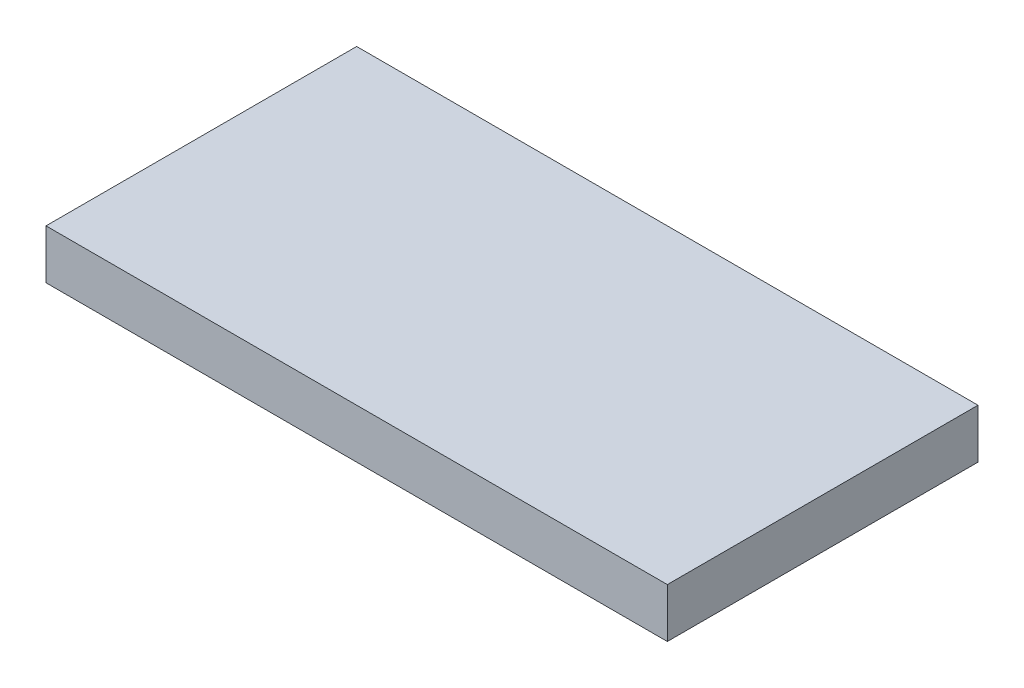
SolidWorks part; units mm, degrees
ref_plane "Front Plane" through (0, 0, 0) normal (0, 0, 1) x (1, 0, 0)
ref_plane "Top Plane" through (0, 0, 0) normal (0, 1, 0) x (1, 0, 0)
ref_plane "Right Plane" through (0, 0, 0) normal (1, 0, 0) x (0, 0, -1)
sketch "Sketch1" plane through (0, 0, 0) normal (0, 1, 0) x (1, 0, 0)
  line L1 (0, 0) -> (80, 0)
  line L2 (0, 0) -> (0, 40)
  line L3 (0, 40) -> (80, 40)
  line L4 (80, 0) -> (80, 40)
  dimension "D1" = 40
  dimension "D2" = 80
extrude "Boss-Extrude1" add sketch "Sketch1" along normal blind 6.35
